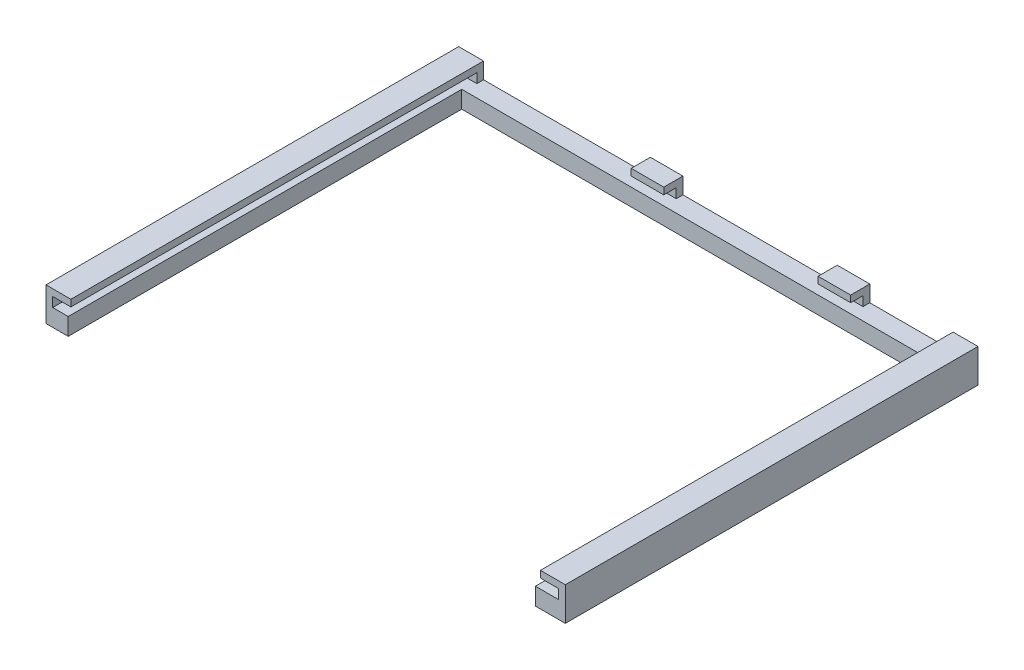
SolidWorks part; units mm, degrees
ref_plane "Front Plane" through (0, 0, 0) normal (0, 0, 1) x (1, 0, 0)
ref_plane "Top Plane" through (0, 0, 0) normal (0, 1, 0) x (1, 0, 0)
ref_plane "Right Plane" through (0, 0, 0) normal (1, 0, 0) x (0, 0, -1)
sketch "Sketch1" plane through (0, 0, 0) normal (0, 0, 1) x (1, 0, 0)
  line L0 (-61.3, -24.209) -> (-61.3, -22.459)
  line L1 (-61.3, -22.459) -> (-67.8, -22.459)
  line L2 (-67.8, -22.459) -> (-67.8, -31.209)
  line L3 (-67.8, -31.209) -> (67.8, -31.209)
  line L4 (67.8, -31.209) -> (67.8, -22.459)
  line L5 (67.8, -22.459) -> (61.3, -22.459)
  line L6 (61.3, -22.459) -> (61.3, -24.209)
  line L7 (61.3, -24.209) -> (66.05, -24.209)
  line L8 (66.05, -24.209) -> (66.05, -26.709)
  line L9 (66.05, -26.709) -> (-66.05, -26.709)
  line L10 (-66.05, -26.709) -> (-66.05, -24.209)
  line L11 (-66.05, -24.209) -> (-61.3, -24.209)
  point P12 (-63.675, -24.209)
  point P15 (0, -31.209)
  dimension "D1" = 132.1
  dimension "D2" = 4.5
  dimension "D3" = 2.5
  dimension "D4" = 1.75
  dimension "D5" = 1.75
  dimension "D6" = 1.75
  dimension "D7" = 4.75
  dimension "D8" = 4.75
extrude "Boss-Extrude1" add sketch "Sketch1" against normal blind 107.75
sketch "Sketch2" plane through (0, -26.709, 0) normal (0, 1, 0) x (1, 0, 0)
  line L0 (66.05, 107.75) -> (-66.05, 107.75) construction
  line L1 (-17.75, 107.75) -> (-9.25, 107.75)
  line L2 (-17.75, 107.75) -> (-17.75, 102.75)
  line L3 (-17.75, 102.75) -> (-9.25, 102.75)
  line L4 (-9.25, 107.75) -> (-9.25, 102.75)
  line L5 (-66.05, 107.75) -> (-66.05, 0) construction
  line L6 (31.05, 107.75) -> (39.55, 107.75)
  line L7 (31.05, 107.75) -> (31.05, 102.75)
  line L8 (31.05, 102.75) -> (39.55, 102.75)
  line L9 (39.55, 107.75) -> (39.55, 102.75)
  line L10 (66.05, 107.75) -> (66.05, 0) construction
  dimension "D1" = 48.3
  dimension "D2" = 8.5
  dimension "D3" = 26.5
  dimension "D4" = 8.5
  dimension "D5" = 5
extrude "Boss-Extrude2" add sketch "Sketch2" along normal blind 4.25
sketch "Sketch3" plane through (0, 0, -102.75) normal (0, 0, 1) x (1, 0, 0)
  line L0 (-9.25, -22.459) -> (-9.25, -26.709) construction
  line L1 (-17.75, -26.709) -> (-9.25, -26.709)
  line L2 (-17.75, -26.709) -> (-17.75, -24.209)
  line L3 (-17.75, -24.209) -> (-9.25, -24.209)
  line L4 (-9.25, -26.709) -> (-9.25, -24.209)
  line L5 (39.55, -22.459) -> (39.55, -26.709) construction
  line L6 (31.05, -26.709) -> (39.55, -26.709)
  line L7 (31.05, -26.709) -> (31.05, -24.209)
  line L8 (31.05, -24.209) -> (39.55, -24.209)
  line L9 (39.55, -26.709) -> (39.55, -24.209)
  dimension "D1" = 2.5
extrude "Cut-Extrude1" cut sketch "Sketch3" against normal blind 3.25
sketch "Sketch4" plane through (66.05, 0, 0) normal (-1, 0, 0) x (0, 0, 1)
  line L0 (-107.75, -24.209) -> (0, -24.209) construction
  line L1 (-107.75, -26.709) -> (-106, -26.709)
  line L2 (-107.75, -26.709) -> (-107.75, -24.209)
  line L3 (-107.75, -24.209) -> (-106, -24.209)
  line L4 (-106, -26.709) -> (-106, -24.209)
  dimension "D1" = 1.75
extrude "Boss-Extrude3" add sketch "Sketch4" along normal up to surface (4.75 mm away) up to face at (61.3, -23.334, -53.875)
sketch "Sketch5" plane through (-66.05, 0, 0) normal (1, 0, 0) x (0, 0, -1)
  line L0 (107.75, -24.209) -> (0, -24.209) construction
  line L1 (107.75, -26.709) -> (106, -26.709)
  line L2 (107.75, -26.709) -> (107.75, -24.209)
  line L3 (107.75, -24.209) -> (106, -24.209)
  line L4 (106, -26.709) -> (106, -24.209)
  dimension "D1" = 1.75
extrude "Boss-Extrude4" add sketch "Sketch5" along normal up to surface (4.75 mm away) up to face at (-61.3, -23.334, -53.875)
sketch "Sketch6" plane through (0, -31.209, 0) normal (0, -1, 0) x (1, 0, 0)
  line L0 (-67.8, -107.75) -> (-67.8, 0) construction
  line L1 (-62, -104) -> (62, -104)
  line L2 (-62, -104) -> (-62, -4)
  line L3 (-62, -4) -> (62, -4)
  line L4 (62, -104) -> (62, -4)
  line L6 (-67.8, 0) -> (67.8, 0) construction
  dimension "D1" = 124
  dimension "D2" = 100
  dimension "D3" = 5.8
  dimension "D4" = 4
sketch "Sketch7" plane through (0, -31.209, 0) normal (0, -1, 0) x (1, 0, 0)
  line L0 (-67.8, -107.75) -> (67.8, -107.75) construction
  line L14 (-62, 4.1474) -> (59.9852, 4.1474)
  line L15 (-62, 4.1474) -> (-62, -102.75)
  line L16 (-62, -102.75) -> (59.9852, -102.75)
  line L17 (59.9852, 4.1474) -> (59.9852, -102.75)
  dimension "D1" = 121.9852
  dimension "D2" = 5
extrude "Cut-Extrude4" cut sketch "Sketch7" against normal up to surface (4.5 mm away) up to face at (5.45, -26.709, -93.4062)
